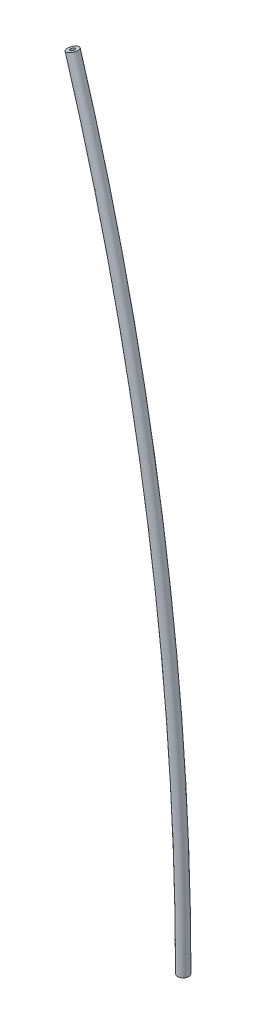
SolidWorks part; units mm, degrees
ref_plane "Front Plane" through (0, 0, 0) normal (0, 0, 1) x (1, 0, 0)
ref_plane "Top Plane" through (0, 0, 0) normal (0, 1, 0) x (1, 0, 0)
ref_plane "Right Plane" through (0, 0, 0) normal (1, 0, 0) x (0, 0, -1)
sketch "Sketch1" plane through (0, 0, 0) normal (0, 0, 1) x (1, 0, 0)
  line L0 (14.517, 0) -> (-14.517, 0) construction
  arc A0 (585.6544, 177.8) -> (612.0489, 0) centre (0, 0) cw
  dimension "D1" = 177.8
  dimension "D2" = 612.0489
  dimension "D3" = 26.3946
sketch "Sketch2" plane through (0, 0, 0) normal (0, 1, 0) x (1, 0, 0)
  circle A0 centre (610.9735, 0) radius 1.3016
  dimension "D1" = 2.6033
sweep "Sweep-Thin1" add profiles "Sketch2" path "Sketch1" parameters "D1"=0.762
ref_plane "Plane1" through (604.5464, 0, 0) normal (1, 0, 0) x (0, 0, -1)
